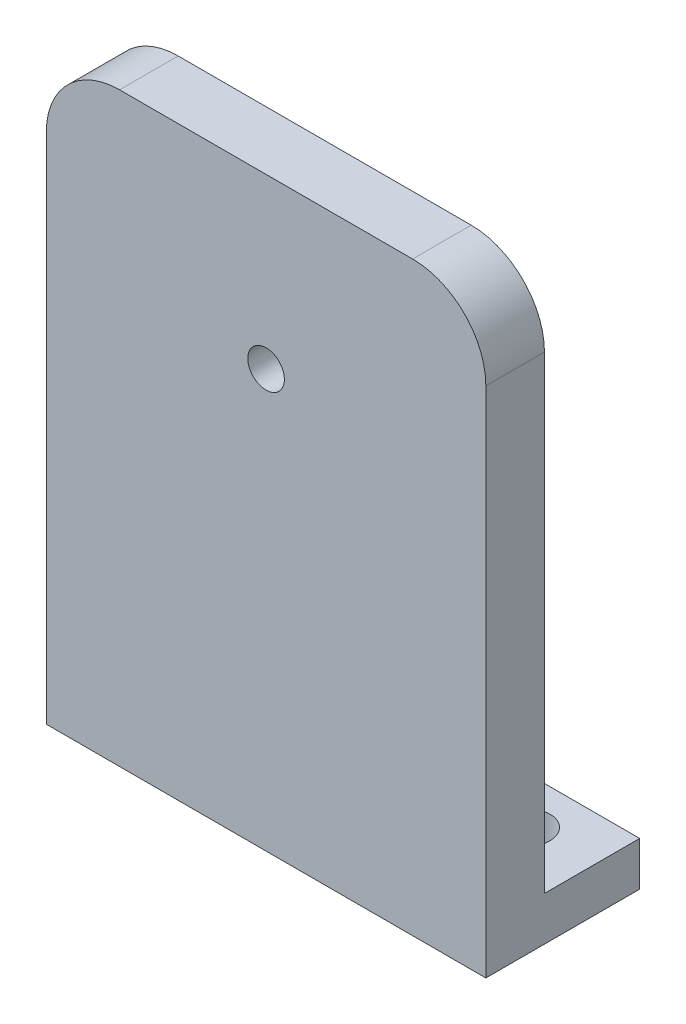
SolidWorks part; units mm, degrees
material "Du"
ref_plane "Front Plane" through (0, 0, 0) normal (0, 0, 1) x (1, 0, 0)
ref_plane "Top Plane" through (0, 0, 0) normal (0, 1, 0) x (1, 0, 0)
ref_plane "Right Plane" through (0, 0, 0) normal (1, 0, 0) x (0, 0, -1)
sketch "Sketch1" plane through (0, 0, 0) normal (0, 1, 0) x (1, 0, 0)
  line L1 (-15, -5.25) -> (15, -5.25)
  line L2 (-15, -5.25) -> (-15, 5.25)
  line L3 (-15, 5.25) -> (15, 5.25)
  line L4 (15, -5.25) -> (15, 5.25)
  line L5 (-15, -5.25) -> (15, 5.25) construction
  line L6 (-15, 5.25) -> (15, -5.25) construction
  point P0 (0, 0)
  dimension "D1" = 30
  dimension "D2" = 10.5
extrude "Boss-Extrude1" add sketch "Sketch1" along normal blind 3
sketch "Sketch2" plane through (0, 3, 0) normal (0, 1, 0) x (1, 0, 0)
  line L0 (15, -5.25) -> (15, 5.25) construction
  line L1 (-15, -5.25) -> (15, -5.25)
  line L2 (-15, -5.25) -> (-15, -1.25)
  line L3 (-15, -1.25) -> (15, -1.25)
  line L4 (15, -5.25) -> (15, -1.25)
  dimension "D1" = 4
extrude "Boss-Extrude2" add sketch "Sketch2" along normal blind 37
sketch "Sketch3" plane through (0, 3, 0) normal (0, 1, 0) x (1, 0, 0)
  line L0 (15, 5.25) -> (-15, 5.25) construction
  line L1 (-15, 5.25) -> (-15, -1.25) construction
  circle A0 centre (-10.5, 2.05) radius 1.575
  dimension "D1" = 3.15
  dimension "D2" = 3.2
  dimension "D3" = 4.5
extrude "Cut-Extrude1" cut sketch "Sketch3" against normal through all
sketch "Sketch4" plane through (0, 3, 0) normal (0, 1, 0) x (1, 0, 0)
  line L1 (15, 5.25) -> (-15, 5.25) construction
  line L2 (15, -1.25) -> (15, 5.25) construction
  circle A0 centre (10.5, 2.05) radius 1.575
  dimension "D1" = 3.15
  dimension "D2" = 3.2
  dimension "D3" = 4.5
extrude "Cut-Extrude2" cut sketch "Sketch4" against normal through all
fillet "Fillet1" radius 5 2 edges at (15, 40, 3.25) (-15, 40, 3.25)
sketch "Sketch5" plane through (0, 0, 5.25) normal (0, 0, 1) x (1, 0, 0)
  line L0 (0, -5.775) -> (0, 5.775) construction
  line L1 (-10, 40) -> (10, 40) construction
  circle A0 centre (0, 28.5) radius 1.25
  dimension "D1" = 2.5
  dimension "D2" = 11.5
extrude "Cut-Extrude3" cut sketch "Sketch5" against normal through all
